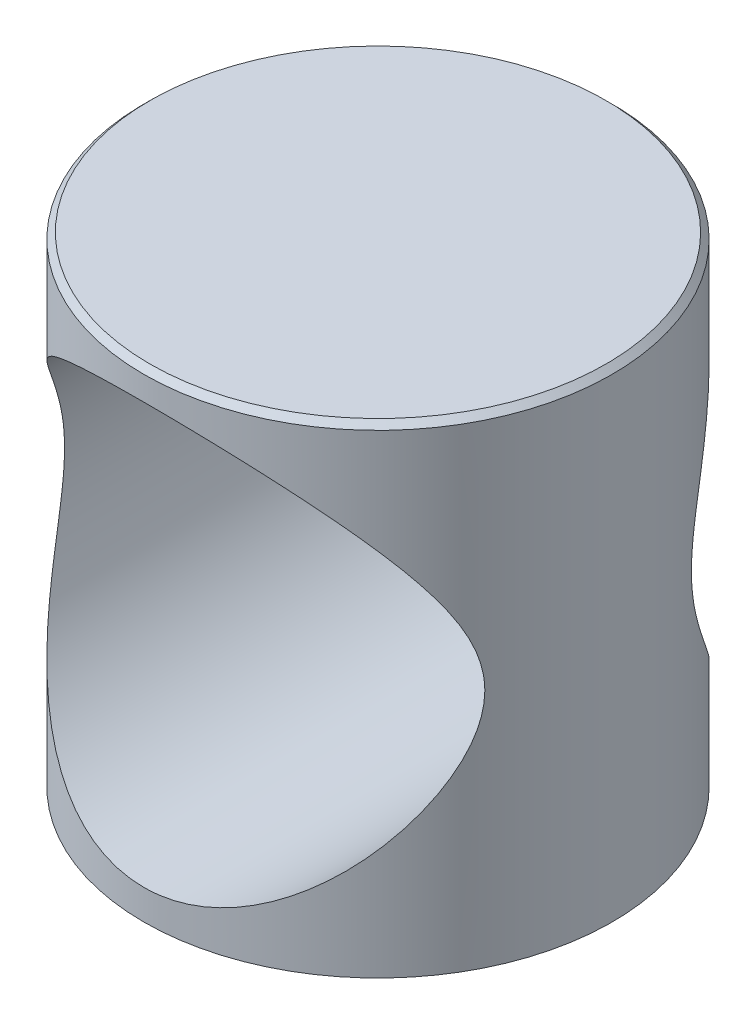
SolidWorks part; units mm, degrees
ref_plane "Frontale" through (0, 0, 0) normal (0, 0, 1) x (1, 0, 0)
ref_plane "Superiore" through (0, 0, 0) normal (0, 1, 0) x (1, 0, 0)
ref_plane "Destro" through (0, 0, 0) normal (1, 0, 0) x (0, 0, -1)
sketch "Schizzo1" plane through (0, 0, 0) normal (0, 1, 0) x (1, 0, 0)
  circle A0 centre (0, 0) radius 39
  dimension "D1" = 78
extrude "Estrusione1" add sketch "Schizzo1" along normal mid plane 80
sketch "Schizzo3" plane through (0, 0, 0) normal (0, 0, 1) x (1, 0, 0)
  circle A0 centre (0, 0) radius 35
  dimension "D1" = 70
extrude "Estrusione3" cut sketch "Schizzo3" against normal mid plane 80
chamfer "Smusso1" distance 1 angle 45 1 edges at (0, 40, 39)
